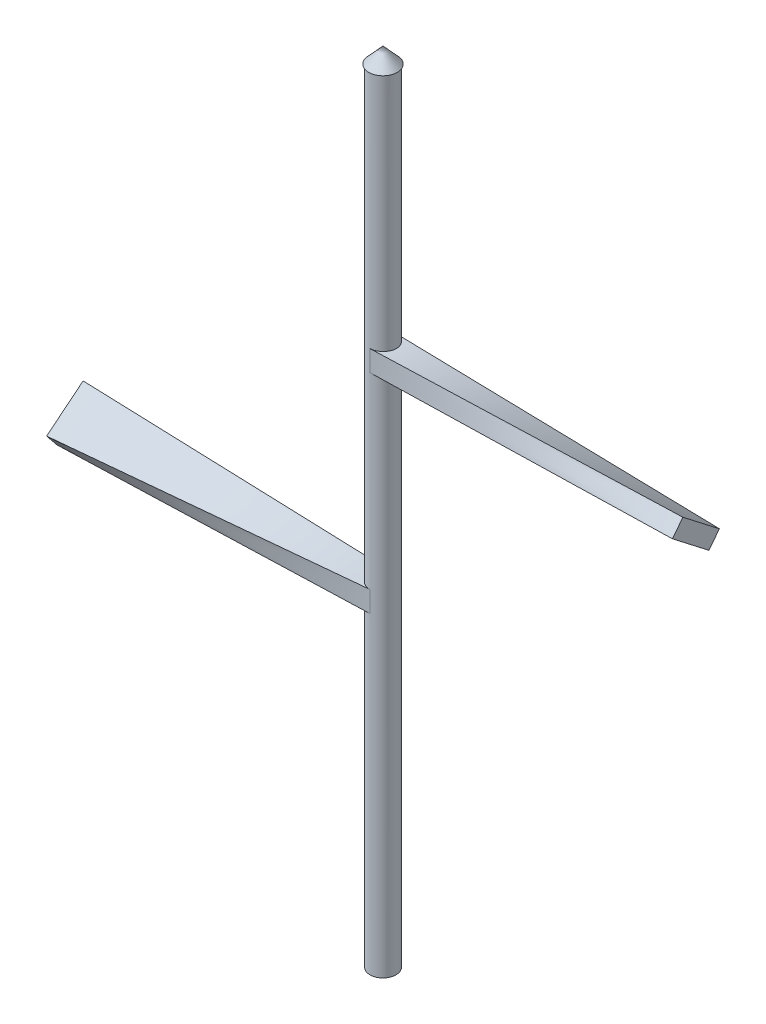
SolidWorks part; units mm, degrees
ref_plane "Front" through (0, 0, 0) normal (0, 0, 1) x (1, 0, 0)
ref_plane "Top" through (0, 0, 0) normal (0, 1, 0) x (1, 0, 0)
ref_plane "Right" through (0, 0, 0) normal (1, 0, 0) x (0, 0, -1)
sketch "Sketch1" plane through (0, 0, 0) normal (0, 1, 0) x (1, 0, 0)
  circle A0 centre (0, 0) radius 2.5
  dimension "D1" = 5
extrude "Boss-Extrude1" add sketch "Sketch1" along normal blind 150
ref_axis "Axis1" through (0, 150, 0) along (0, -1, 0)
sketch "Sketch5" plane through (0, 0, 0) normal (1, 0, 0) x (0, 0, -1)
  line L0 (0, 150) -> (0, 156)
  line L1 (2.5, 150) -> (-2.5, 150) construction
  line L2 (0, 156) -> (0, 153)
  line L3 (0, 153) -> (-2.75, 150)
  line L4 (-2.75, 150) -> (0, 150)
  dimension "D1" = 3
revolve "Revolve9" add sketch "Sketch5" angle 360 about axis through (0, 150, 0) along (0, -1, 0)
ref_plane "Plane1" through (60, 0, 0) normal (1, 0, 0) x (0, 0, -1)
ref_plane "Plane2" through (-60, 0, 0) normal (1, 0, 0) x (0, 0, -1)
ref_plane "Plane3" through (0, 0, 60) normal (0, 0, 1) x (1, 0, 0)
ref_plane "Plane4" through (0, 0, -60) normal (0, 0, 1) x (1, 0, 0)
sketch "Sketch17" plane through (0, 0, 0) normal (0, -1, 0) x (1, 0, 0)
  line L0 (-2.4359, 0.6055) -> (-1.3268, -2.1307)
  arc A0 (-1.3268, -2.1307) -> (-2.4359, 0.6055) centre (0, 0) cw
  circle M1 centre (0, 0) radius 2.5
extrude "Cut-Extrude1" cut sketch "Sketch17" against normal blind 10 contours L0 M1
sketch "Sketch18" plane through (0, 0, 0) normal (1, 0, 0) x (0, 0, -1)
  line L0 (2.5, 60) -> (-2.5, 60)
  line L1 (2.5, 60) -> (2.5, 64)
  line L2 (-2.5, 60) -> (-2.5, 64)
  line L3 (2.5, 64) -> (-2.5, 64)
  line L4 (2.5, 0) -> (2.5, 150) construction
  line L5 (-2.5, 150) -> (-2.5, 0) construction
  line L6 (-2.5, 0) -> (2.5, 0) construction
  dimension "D1" = 0
  dimension "D2" = 60
  dimension "D3" = 4
sketch "Sketch19" plane through (-60, 0, 0) normal (1, 0, 0) x (0, 0, -1)
  line L0 (4.5, 63.668) -> (-2.5, 58)
  line L1 (4.5, 63.668) -> (2.5, 66.138)
  line L2 (-2.5, 58) -> (-4.5, 60.47)
  line L3 (2.5, 66.138) -> (-4.5, 60.47)
  line L4 (-2.5, 60) -> (-2.5, 64) construction
  line L5 (-2.5, 150) -> (-2.5, 0) construction
  line L6 (2.5, 0) -> (2.5, 150) construction
  point P8 (0, 0)
  dimension "D1" = 2
  dimension "D2" = 0
  dimension "D3" = 0
  dimension "D4" = 2
loft "Loft1" add profiles "Sketch18", "Sketch19"
sketch "Sketch20" plane through (0, 0, 0) normal (1, 0, 0) x (0, 0, -1)
  line L0 (2.5, 100) -> (-2.5, 100)
  line L1 (2.5, 100) -> (2.5, 104)
  line L2 (-2.5, 100) -> (-2.5, 104)
  line L3 (2.5, 104) -> (-2.5, 104)
  line L4 (2.5, 64) -> (2.5, 150) construction
  line L5 (-2.5, 150) -> (-2.5, 64) construction
  line L6 (-2.5, 0) -> (2.5, 0) construction
  dimension "D1" = 100
  dimension "D2" = 4
sketch "Sketch21" plane through (60, 0, 0) normal (1, 0, 0) x (0, 0, -1)
  line L0 (-2.5, 106) -> (-4.5, 103.4142)
  line L1 (-2.5, 106) -> (4.5, 100.5858)
  line L2 (-4.5, 103.4142) -> (2.5, 98)
  line L3 (4.5, 100.5858) -> (2.5, 98)
  line L4 (-2.5, 150) -> (-2.5, 64) construction
  line L5 (-2.5, 100) -> (-2.5, 104) construction
  dimension "D1" = 2
  dimension "D2" = 2
  dimension "D3" = 0
  dimension "D4" = 0
  dimension "D5" = 2
loft "Loft2" add profiles "Sketch20", "Sketch21"
